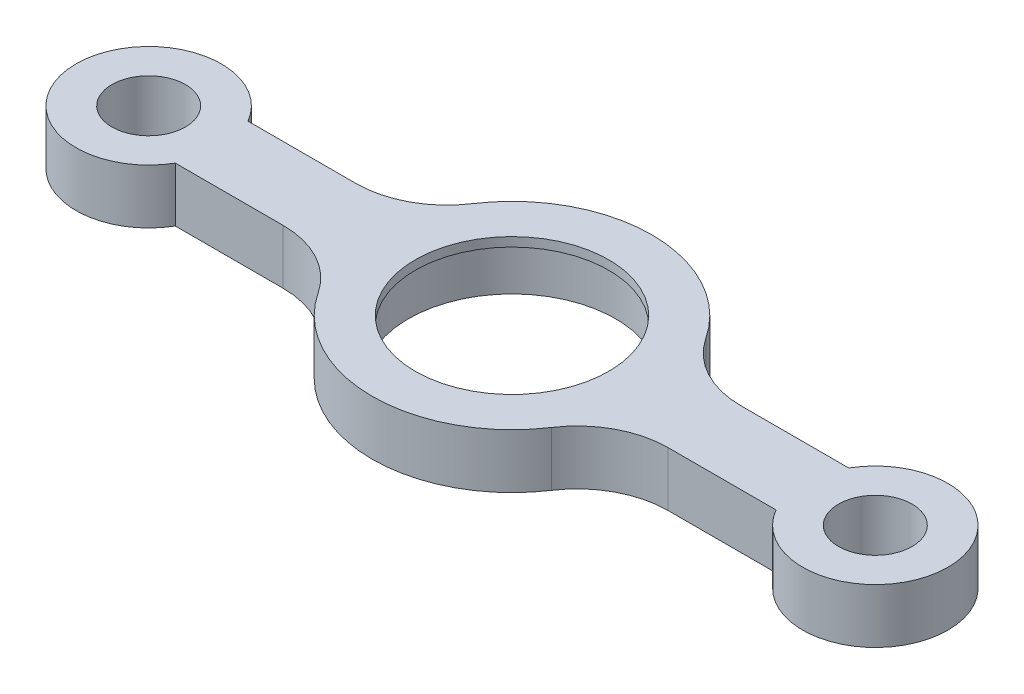
SolidWorks part; units mm, degrees
material "ABS"
ref_plane "Plano frontal" through (0, 0, 0) normal (0, 0, 1) x (1, 0, 0)
ref_plane "Plano superior" through (0, 0, 0) normal (0, 1, 0) x (1, 0, 0)
ref_plane "Plano direito" through (0, 0, 0) normal (1, 0, 0) x (0, 0, -1)
sketch "Esboço1" plane through (0, 0, 0) normal (0, 1, 0) x (1, 0, 0)
  line L0 (-40, 0) -> (40, 0) construction
  line L1 (-33.0718, 4) -> (-21.1934, 4)
  line L2 (-33.0718, -4) -> (-21.1934, -4)
  line L3 (21.1934, 4) -> (33.0718, 4)
  line L4 (21.1934, -4) -> (33.0718, -4)
  arc A0 (-33.0718, 4) -> (-33.0718, -4) centre (-40, 0) ccw
  arc A1 (33.0718, -4) -> (33.0718, 4) centre (40, 0) ccw
  circle A2 centre (40, 0) radius 4.05
  circle A3 centre (-40, 0) radius 4.05
  arc A4 (-12.8495, -8.4882) -> (12.8495, -8.4882) centre (0, 0) ccw
  arc A5 (12.8495, 8.4882) -> (-12.8495, 8.4882) centre (0, 0) ccw
  circle A6 centre (0, 0) radius 11.4
  arc A7 (-12.8495, -8.4882) -> (-21.1934, -4) centre (-21.1934, -14) ccw
  arc A8 (21.1934, -4) -> (12.8495, -8.4882) centre (21.1934, -14) ccw
  arc A9 (21.1934, 4) -> (12.8495, 8.4882) centre (21.1934, 14) cw
  arc A10 (-12.8495, 8.4882) -> (-21.1934, 4) centre (-21.1934, 14) cw
  point P4 (0, 0)
  point P22 (14.8714, 4)
  dimension "D2" = 8.1
  dimension "D3" = 16
  dimension "D5" = 4
  dimension "D6" = 22.8
  dimension "D7" = 10
  dimension "D1" = 80
  dimension "D4" = 8
extrude "Ressalto-extrusão1" add sketch "Esboço1" along normal blind 6
sketch "Esboço2" plane through (0, 6, 0) normal (0, 1, 0) x (1, 0, 0)
  circle A0 centre (0, 0) radius 10.65
  circle A1 centre (0, 0) radius 11.4
  circle A2 centre (0, 0) radius 11.4 construction
  dimension "D1" = 0.75
extrude "Ressalto-extrusão2" add sketch "Esboço2" against normal blind 1
